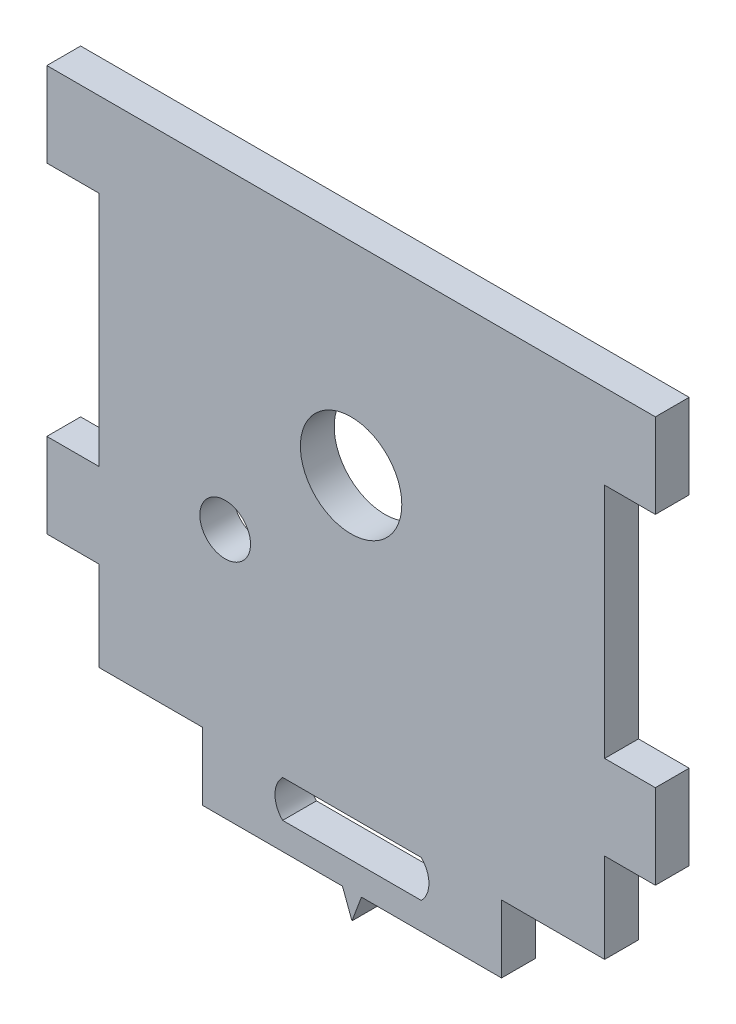
SolidWorks part; units mm, degrees
ref_plane "前视基准面" through (0, 0, 0) normal (0, 0, 1) x (1, 0, 0)
ref_plane "上视基准面" through (0, 0, 0) normal (0, 1, 0) x (1, 0, 0)
ref_plane "右视基准面" through (0, 0, 0) normal (1, 0, 0) x (0, 0, -1)
sketch "草图1" plane through (0, 0, 0) normal (0, 0, 1) x (1, 0, 0)
  line L0 (0, 0) -> (0, 5)
  line L1 (0, 5) -> (-3, 5)
  line L2 (0, 0) -> (-3, 0)
  line L3 (-3, 0) -> (-3, -14)
  line L4 (-3, -14) -> (0, -14)
  line L5 (0, -14) -> (0, -19)
  line L6 (0, -19) -> (-3, -19)
  line L7 (-3, 5) -> (-33, 5)
  line L8 (-36, -19) -> (-33, -19)
  line L9 (-18, 5) -> (-18, 0.8851) construction
  line L10 (-36, -14) -> (-36, -19)
  line L11 (-33, -14) -> (-36, -14)
  line L12 (-33, 0) -> (-33, -14) construction
  line L13 (-36, 0) -> (-33, 0)
  line L14 (-36, 5) -> (-33, 5)
  line L15 (-36, 0) -> (-36, 5)
  line L17 (-33, -7) -> (-3, -7) construction
  line L18 (-33, -19) -> (-33, -32) construction
  line L21 (-33, 0) -> (-32.9, 0)
  line L22 (-32.9, 0) -> (-32.9, -14)
  line L23 (-32.9, -14) -> (-33, -14)
  line L24 (-33, -19) -> (-32.9, -19)
  line L29 (-3, -19) -> (-3, -24.3)
  line L31 (-3, -24.3) -> (-9.1, -24.3)
  line L33 (-22.05, -24.5) -> (-13.85, -24.5)
  line L35 (-22.05, -26.7) -> (-13.85, -26.7)
  line L37 (-22.05, -24.5) -> (-13.85, -26.7) construction
  line L38 (-22.05, -26.7) -> (-13.85, -24.5) construction
  line L39 (-17.95, -25.6) -> (-17.95, -23.6631) construction
  line L41 (-32.9, -24.3) -> (-26.8, -24.3)
  line L43 (-32.9, -19) -> (-32.9, -24.3)
  line L44 (-9.1, -24.3) -> (-17.95, -24.3) construction
  line L45 (-9.1, -24.3) -> (-9.1, -28.3)
  line L47 (-26.8, -28.3) -> (-26.8, -24.3)
  line L49 (-17.95, -29.8) -> (-17.3884, -28.3)
  line L50 (-17.3884, -28.3) -> (-9.1, -28.3)
  line L51 (-18.5116, -28.3) -> (-26.8, -28.3)
  line L52 (-17.95, -29.8) -> (-18.5116, -28.3)
  circle A0 centre (-18, -7) radius 3
  circle A1 centre (-25.45, -13.5) radius 1.5
  arc A2 (-22.05, -26.7) -> (-22.05, -24.5) centre (-20.95, -25.6) cw
  arc A3 (-13.85, -26.7) -> (-13.85, -24.5) centre (-14.95, -25.6) ccw
extrude "凸台-拉伸1" add sketch "草图1" along normal blind 2
